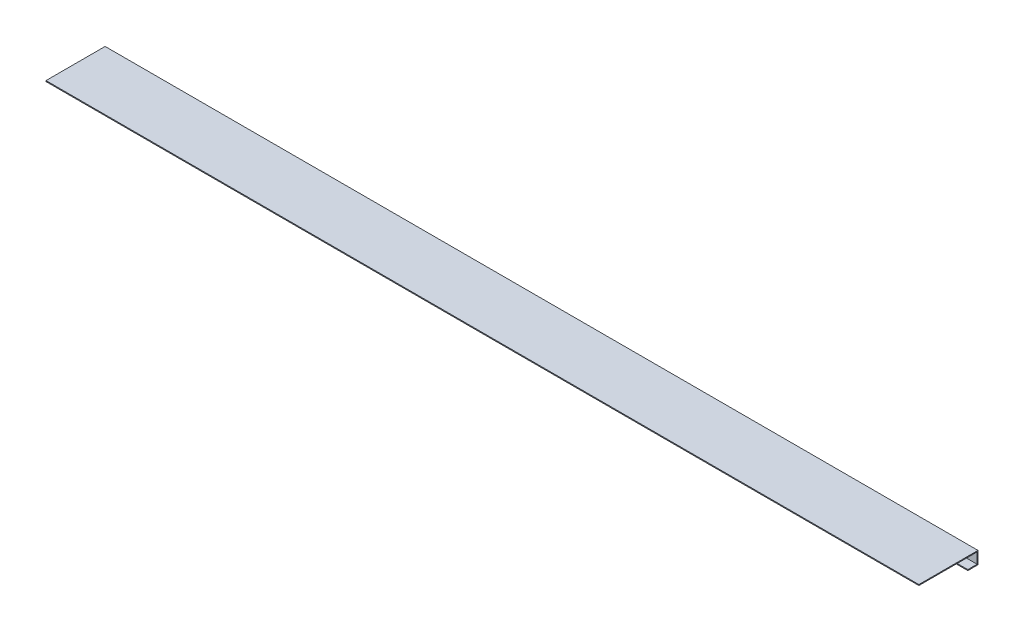
SolidWorks part; units mm, degrees
ref_plane "Front Plane" through (0, 0, 0) normal (0, 0, 1) x (1, 0, 0)
ref_plane "Top Plane" through (0, 0, 0) normal (0, 1, 0) x (1, 0, 0)
ref_plane "Right Plane" through (0, 0, 0) normal (1, 0, 0) x (0, 0, -1)
sketch "Sketch1" plane through (0, 0, 0) normal (1, 0, 0) x (0, 0, -1)
  line L0 (0, 0) -> (128, 0)
  line L1 (128, 0) -> (128, -27)
  line L2 (128, -27) -> (106, -27)
  line L3 (0, -2) -> (126, -2)
  line L4 (126, -2) -> (126, -25)
  line L5 (126, -25) -> (106, -25)
  line L6 (0, 0) -> (0, -2)
  line L7 (106, -27) -> (106, -25)
  dimension "D1" = 2
  dimension "D2" = 128
  dimension "D3" = 27
  dimension "D4" = 22
extrude "Boss-Extrude1" add sketch "Sketch1" along normal blind 1890
equation "\"door_base_long7_R1_R_open_Single_height\"=1890.0"
equation "\"D1@Boss-Extrude1\"= \"door_base_long7_L1_R_open_Single_height\""
equation "\"CarBeamWidth\"=700.0"
equation "\"WheelWidth\"=650.0"
equation "\"Wheel_FrontBoxDistance\"=1390.0"
equation "\"MetalSheet_3mm_length\"=5030.0"
equation "\"MetalSheet_3mm_width\"=1923.0"
equation "\"MetalSheet_3mm_FloorCut_L_length\"=1764.0"
equation "\"MetalSheet_3mm_FloorCut_L_disdance\"=1665.0"
equation "\"MetalSheet_3mm_FloorCut_R_length\"=1764.0"
equation "\"MetalSheet_3mm_FloorCut_R_disdance\"=1665.0"
equation "\"indoorHeight\"=1940.0"
equation "\"haveDoor_R\"=1"
equation "\"side_door_bottom_R_3mm_length\"=1934.0"
equation "\"1Bar_Side_RF_3mm_length\"=1493.0"
equation "\"1Bar_Side_RB_3mm_length\"=1493.0"
equation "\"DoorSeparator_RF_3mm_withHinge_toFrontDistance\"=1673.0"
equation "\"DoorSeparator_RF_3mm_withHinge_exist\"=1"
equation "\"DoorSeparator_RB_3mm_withHinge_toFrontDistance\"=3427.0"
equation "\"DoorSeparator_RB_3mm_withHinge_exist\"=1"
equation "\"Door_R1_L_open_Single_toFrontDistance\"=2547.5"
equation "\"Door_R1_L_open_Single_exist\"=1"
equation "\"door_base_long7_R1_L_open_Single_height\"=1890.0"
equation "\"door_base_short7_R1_L_open_Single_height\"=1890.0"
equation "\"door_base_short7_R1_L_open_Single_width\"=864"
equation "\"Door_R1_R_open_Single_toFrontDistance\"=3422.0"
equation "\"Door_R1_R_open_Single_exist\"=1"
equation "\"door_base_short7_R1_R_open_Single_height\"=1890.0"
equation "\"door_base_short7_R1_R_open_Single_width\"=864"
equation "\"x\"=66.0"
equation "\"da\"=62.0"
equation "\"SquareTube_length\"=1923.0"
equation "\"channelSteel_length\"=5030.0"
equation "\"SquareTube_inFront_AvgDistance\"=285.0"
equation "\"SquareTube_inFront_TotalCount\"=5"
equation "\"SquareTube_inFront1_cutDepth50_R\"=0.5"
equation "\"SquareTube_inFront1_cutDepth50_L\"=0.5"
equation "\"SquareTube_inFront2_cutDepth50_R\"=0.5"
equation "\"SquareTube_inFront2_cutDepth50_L\"=0.5"
equation "\"SquareTube_inFront3_cutDepth50_R\"=0.5"
equation "\"SquareTube_inFront3_cutDepth50_L\"=0.5"
equation "\"SquareTube_inFront4_cutDepth50_R\"=0.5"
equation "\"SquareTube_inFront4_cutDepth50_L\"=0.5"
equation "\"SquareTube_inFront5_cutDepth50_R\"=50"
equation "\"SquareTube_inFront5_cutDepth50_L\"=50"
equation "\"SquareTube_inFront6_cutDepth50_R\"=50"
equation "\"SquareTube_inFront6_cutDepth50_L\"=50"
equation "\"SquareTube_inFront7_cutDepth50_R\"=50"
equation "\"SquareTube_inFront7_cutDepth50_L\"=50"
equation "\"SquareTube_inFront8_cutDepth50_R\"=50"
equation "\"SquareTube_inFront8_cutDepth50_L\"=50"
equation "\"SquareTube_inFront9_cutDepth50_R\"=50"
equation "\"SquareTube_inFront9_cutDepth50_L\"=50"
equation "\"SquareTube_inFront10_cutDepth50_R\"=50"
equation "\"SquareTube_inFront10_cutDepth50_L\"=50"
equation "\"SquareTube_inFront11_cutDepth50_R\"=50"
equation "\"SquareTube_inFront11_cutDepth50_L\"=50"
equation "\"SquareTube_inFront12_cutDepth50_R\"=50"
equation "\"SquareTube_inFront12_cutDepth50_L\"=50"
equation "\"SquareTube_inFront13_cutDepth50_R\"=50"
equation "\"SquareTube_inFront13_cutDepth50_L\"=50"
equation "\"SquareTube_inFront14_cutDepth50_R\"=50"
equation "\"SquareTube_inFront14_cutDepth50_L\"=50"
equation "\"SquareTube_inBack_AvgDistance\"=333.125"
equation "\"SquareTube_inBack_TotalCount\"=9"
equation "\"SquareTube_inBack1_cutDepth50_R\"=50"
equation "\"SquareTube_inBack1_cutDepth50_L\"=50"
equation "\"SquareTube_inBack2_cutDepth50_R\"=50"
equation "\"SquareTube_inBack2_cutDepth50_L\"=50"
equation "\"SquareTube_inBack3_cutDepth50_R\"=50"
equation "\"SquareTube_inBack3_cutDepth50_L\"=50"
equation "\"SquareTube_inBack4_cutDepth50_R\"=50"
equation "\"SquareTube_inBack4_cutDepth50_L\"=50"
equation "\"SquareTube_inBack5_cutDepth50_R\"=50"
equation "\"SquareTube_inBack5_cutDepth50_L\"=50"
equation "\"SquareTube_inBack6_cutDepth50_R\"=0.5"
equation "\"SquareTube_inBack6_cutDepth50_L\"=0.5"
equation "\"SquareTube_inBack7_cutDepth50_R\"=0.5"
equation "\"SquareTube_inBack7_cutDepth50_L\"=0.5"
equation "\"SquareTube_inBack8_cutDepth50_R\"=0.5"
equation "\"SquareTube_inBack8_cutDepth50_L\"=0.5"
equation "\"boxLength\"=5100.0"
equation "\"boxWidth\"=1930.0"
equation "\"indoorHeight_para\"=25.0"
equation "\"rearLightHeight_para\"=265.0"
equation "\"doorColumnBar_A_FR_3mm_length_Cut\"=2310.0"
equation "\"A\"=0.0"
equation "\"side_door_bottom_R_3mm_toFrontDistance\"=1583.0"
equation "\"door_base_double_BL_height\"=1890.0"
equation "\"door_base_short7_BL_Single_height\"=1890.0"
equation "\"door_base_short7_BL_Single_width\"=864"
equation "\"door_base_long7_BR_Single_height\"=1890.0"
equation "\"door_base_short7_BR_Single_height\"=1890.0"
equation "\"door_base_short7_BR_Single_width\"=864"
equation "\"doorColumnBar_A_FL_3mm_length_Cut\"=2310.0"
equation "\"B\"=0.0"
equation "\"haveDoor_L\"=1"
equation "\"side_door_bottom_L_3mm_length\"=1934.0"
equation "\"side_door_bottom_L_3mm_toFrontDistance\"=1583.0"
equation "\"1Bar_Side_LF_3mm_length\"=1493.0"
equation "\"1Bar_Side_LB_3mm_length\"=1493.0"
equation "\"DoorSeparator_LF_3mm_withHinge_toFrontDistance\"=1673.0"
equation "\"DoorSeparator_LF_3mm_withHinge_exist\"=1"
equation "\"DoorSeparator_LB_3mm_withHinge_toFrontDistance\"=3427.0"
equation "\"DoorSeparator_LB_3mm_withHinge_exist\"=1"
equation "\"Door_L1_L_open_Single_toFrontDistance\"=3422.0"
equation "\"Door_L1_L_open_Single_exist\"=1"
equation "\"door_base_long7_L1_L_open_Single_height\"=1890.0"
equation "\"door_base_short7_L1_L_open_Single_height\"=1890.0"
equation "\"door_base_short7_L1_L_open_Single_width\"=864"
equation "\"Door_L1_R_open_Single_toFrontDistance\"=2547.5"
equation "\"Door_L1_R_open_Single_exist\"=1"
equation "\"door_base_long7_L1_R_open_Single_height\"=1890.0"
equation "\"door_base_short7_L1_R_open_Single_height\"=1890.0"
equation "\"door_base_short7_L1_R_open_Single_width\"=864"
